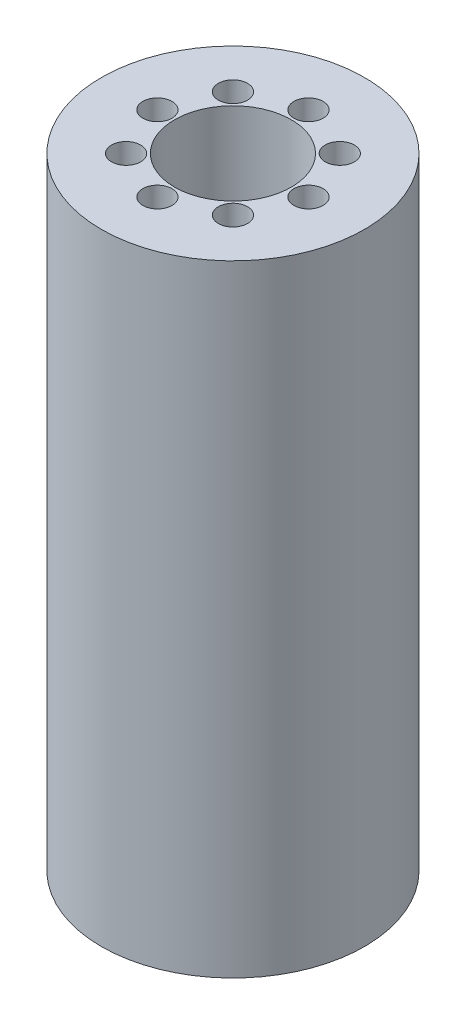
SolidWorks part; units mm, degrees
ref_plane "前视基准面" through (0, 0, 0) normal (0, 0, 1) x (1, 0, 0)
ref_plane "上视基准面" through (0, 0, 0) normal (0, 1, 0) x (1, 0, 0)
ref_plane "右视基准面" through (0, 0, 0) normal (1, 0, 0) x (0, 0, -1)
sketch "草图1" plane through (0, 0, 0) normal (0, 1, 0) x (1, 0, 0)
  circle A0 centre (0, 0) radius 67.58
  circle A1 centre (0, 0) radius 30
  dimension "D1" = 135.16
  dimension "D2" = 60
extrude "凸台-拉伸1" add sketch "草图1" along normal blind 319
sketch "草图2" plane through (0, 319, 0) normal (0, 1, 0) x (1, 0, 0)
  circle A0 centre (0, 0) radius 38.8 construction
  circle A1 centre (-38.8, 0) radius 7.5
  circle A2 centre (-27.4357, 27.4357) radius 7.5
  circle A3 centre (0, 38.8) radius 7.5
  circle A4 centre (27.4357, 27.4357) radius 7.5
  circle A5 centre (38.8, 0) radius 7.5
  circle A6 centre (27.4357, -27.4357) radius 7.5
  circle A7 centre (0, -38.8) radius 7.5
  circle A8 centre (-27.4357, -27.4357) radius 7.5
  dimension "D1" = 15
  dimension "D2" = 77.6
  dimension "D3" = 8
extrude "切除-拉伸1" cut sketch "草图2" against normal up to next
